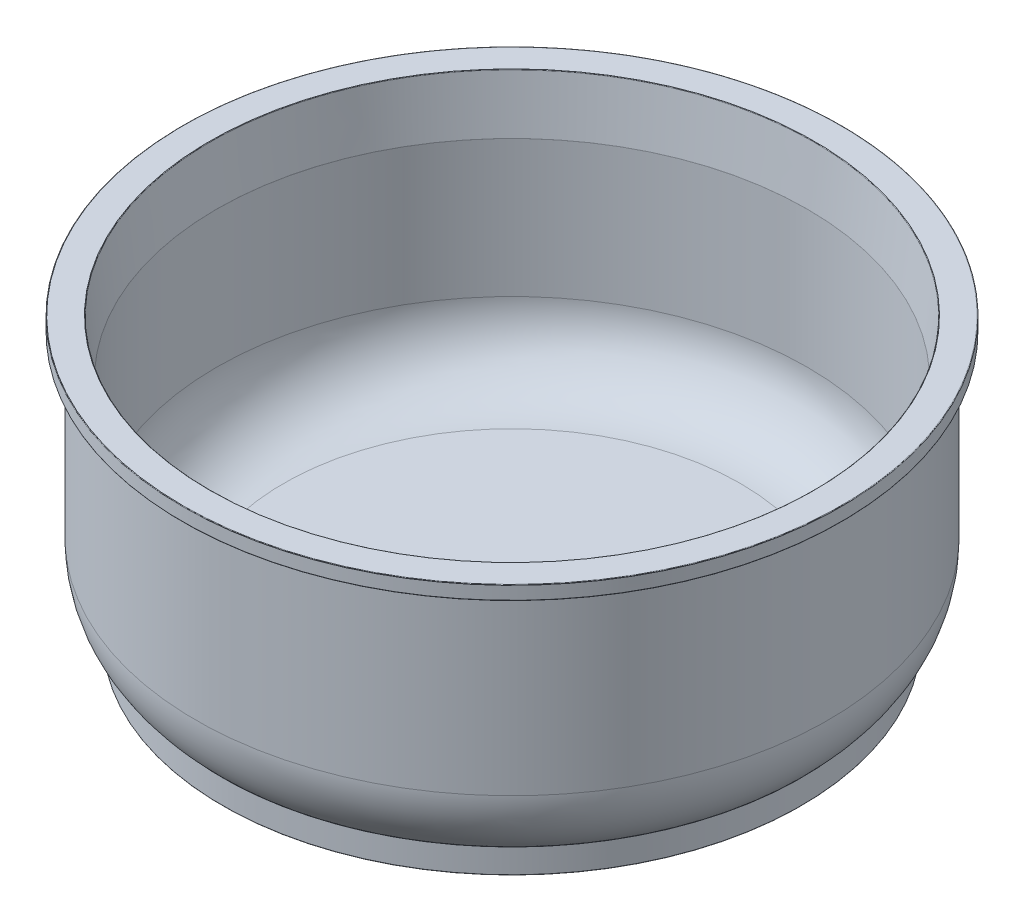
SolidWorks part; units mm, degrees
material "PET"
ref_plane "Front Plane" through (0, 0, 0) normal (0, 0, 1) x (1, 0, 0)
ref_plane "Top Plane" through (0, 0, 0) normal (0, 1, 0) x (1, 0, 0)
ref_plane "Right Plane" through (0, 0, 0) normal (1, 0, 0) x (0, 0, -1)
sketch "Sketch1" plane through (0, 0, 0) normal (0, 0, 1) x (1, 0, 0)
  line L0 (0, 0) -> (0, 167) construction
  line L1 (0, 0) -> (136.11, 0)
  line L2 (188.5, 52.39) -> (188.5, 158.7)
  line L3 (0, 12.39) -> (136.11, 12.39)
  line L4 (176.11, 52.39) -> (176.11, 134)
  line L5 (164.2, 8.1671) -> (164.2, 0)
  line L6 (164.2, 0) -> (172.5, 0)
  line L7 (172.5, 0) -> (172.5, 14.7007)
  line L8 (188.5, 158.7) -> (196.5, 158.7)
  line L9 (196.5, 158.7) -> (196.5, 167)
  line L10 (196.5, 167) -> (180, 167)
  line L11 (180, 167) -> (176.11, 134)
  line L12 (0, 12.39) -> (0, 0)
  arc A0 (136.11, 0) -> (188.5, 52.39) centre (136.11, 52.39) ccw
  arc A1 (136.11, 12.39) -> (176.11, 52.39) centre (136.11, 52.39) ccw
  dimension "D3" = 393
  dimension "D7" = 40
  dimension "D1" = 12.39
  dimension "D2" = 167
  dimension "D4" = 377
  dimension "D5" = 345
  dimension "D6" = 8.3
  dimension "D8" = 8.3
  dimension "D9" = 33
  dimension "D10" = 16.5
revolve "Revolve1" add sketch "Sketch1" angle 360 about L0
fillet "Fillet1" radius 0.3 9 edges at (0, 167, -180) (0, 134, -176.11) (0, 8.1671, -164.2) (0, 0, -164.2) (0, 0, -172.5) (0, 14.7007, -172.5) (0, 158.7, -196.5) (0, 167, -196.5) (0, 158.7, -188.5)
